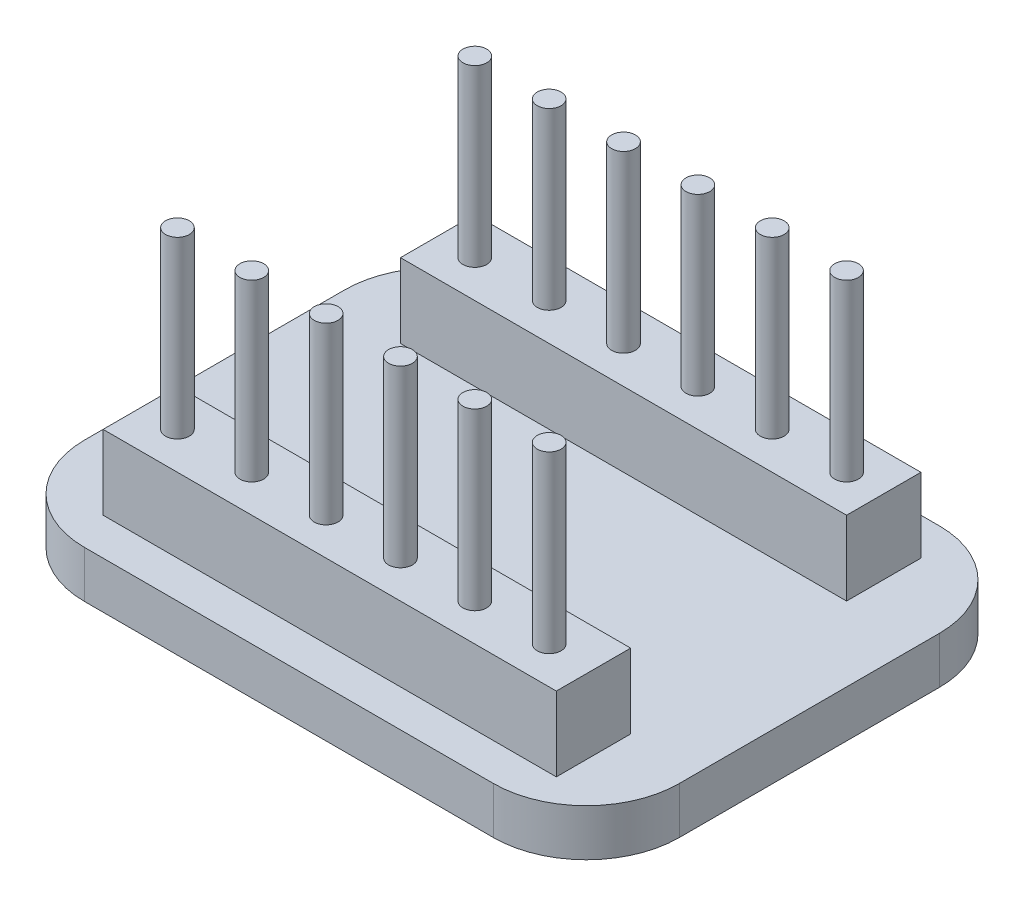
SolidWorks part; units mm, degrees
ref_plane "Front Plane" through (0, 0, 0) normal (0, 0, 1) x (1, 0, 0)
ref_plane "Top Plane" through (0, 0, 0) normal (0, 1, 0) x (1, 0, 0)
ref_plane "Right Plane" through (0, 0, 0) normal (1, 0, 0) x (0, 0, -1)
sketch "Sketch1" plane through (0, 0, 0) normal (0, 1, 0) x (1, 0, 0)
  line L1 (-6.985, -7.62) -> (6.985, -7.62)
  line L2 (-10.16, -4.445) -> (-10.16, 4.445)
  line L3 (-6.985, 7.62) -> (6.985, 7.62)
  line L4 (10.16, -4.445) -> (10.16, 4.445)
  line L5 (-10.16, -7.62) -> (10.16, 7.62) construction
  line L6 (-10.16, 7.62) -> (10.16, -7.62) construction
  arc A0 (-10.16, 4.445) -> (-6.985, 7.62) centre (-6.985, 4.445) cw
  arc A1 (10.16, 4.445) -> (6.985, 7.62) centre (6.985, 4.445) ccw
  arc A2 (-10.16, -4.445) -> (-6.985, -7.62) centre (-6.985, -4.445) ccw
  arc A3 (6.985, -7.62) -> (10.16, -4.445) centre (6.985, -4.445) ccw
  point P0 (0, 0)
  dimension "D3" = 3.175
  dimension "D1" = 15.24
  dimension "D2" = 20.32
extrude "Boss-Extrude1" add sketch "Sketch1" along normal blind 1.6002 contours L3 A1 L4 A3 L1 A2 L2 A0
sketch "Sketch2" plane through (0, 1.6002, 0) normal (0, 1, 0) x (1, 0, 0)
  line L0 (-6.35, 5.08) -> (-6.35, -5.08) construction
  line L1 (0, 0) -> (-6.35, 0) construction
  circle A0 centre (-6.35, 5.08) radius 0.508
  circle A1 centre (-6.35, -5.08) radius 0.508
  dimension "D2" = 1.016
  dimension "D1" = 10.16
  dimension "D3" = 6.35
extrude "Cut-Extrude1" cut sketch "Sketch2" against normal through all both and the other way through all
pattern_linear "LPattern1" count 6 spacing 2.54 along (1, 0, 0) of "Cut-Extrude1"
sketch "Sketch3" plane through (0, 1.6002, 0) normal (0, 1, 0) x (1, 0, 0)
  line L0 (-6.35, 5.08) -> (-6.35, 6.35) construction
  line L1 (-7.62, 6.35) -> (7.62, 6.35)
  line L2 (-7.62, 6.35) -> (-7.62, 3.81)
  line L3 (-7.62, 3.81) -> (7.62, 3.81)
  line L4 (7.62, 6.35) -> (7.62, 3.81)
  line L5 (-7.62, -3.81) -> (7.8642, -3.81)
  line L6 (-7.62, -3.81) -> (-7.62, -6.35)
  line L7 (-7.62, -6.35) -> (7.8642, -6.35)
  line L8 (7.8642, -3.81) -> (7.8642, -6.35)
  line L9 (-6.35, 5.08) -> (-6.35, 3.81) construction
  line L10 (-6.35, 5.08) -> (-7.62, 5.08) construction
  line L11 (6.35, 5.08) -> (7.62, 5.08) construction
  line L12 (-6.35, -5.08) -> (-6.35, -3.81) construction
  dimension "D1" = 1.27
extrude "Boss-Extrude2" add sketch "Sketch3" along normal blind 2.54
sketch "Sketch4" plane through (0, 4.1402, 0) normal (0, 1, 0) x (1, 0, 0)
  line L0 (-6.35, 5.08) -> (-7.62, 5.08) construction
  line L1 (-7.62, 6.35) -> (-7.62, 3.81) construction
  line L2 (-6.35, 5.08) -> (-6.35, 3.81) construction
  line L3 (-7.62, 3.81) -> (7.62, 3.81) construction
  line L4 (-6.35, -5.08) -> (-7.62, -5.08) construction
  line L5 (-7.62, -3.81) -> (-7.62, -6.35) construction
  circle A0 centre (-6.35, 5.08) radius 0.4064
  circle A1 centre (-6.35, -5.08) radius 0.4064
  dimension "D1" = 0.8128
extrude "Boss-Extrude3" add sketch "Sketch4" along normal blind 5.969
pattern_linear "LPattern2" count 6 spacing 2.54 along (1, 0, 0) of "Boss-Extrude3"
